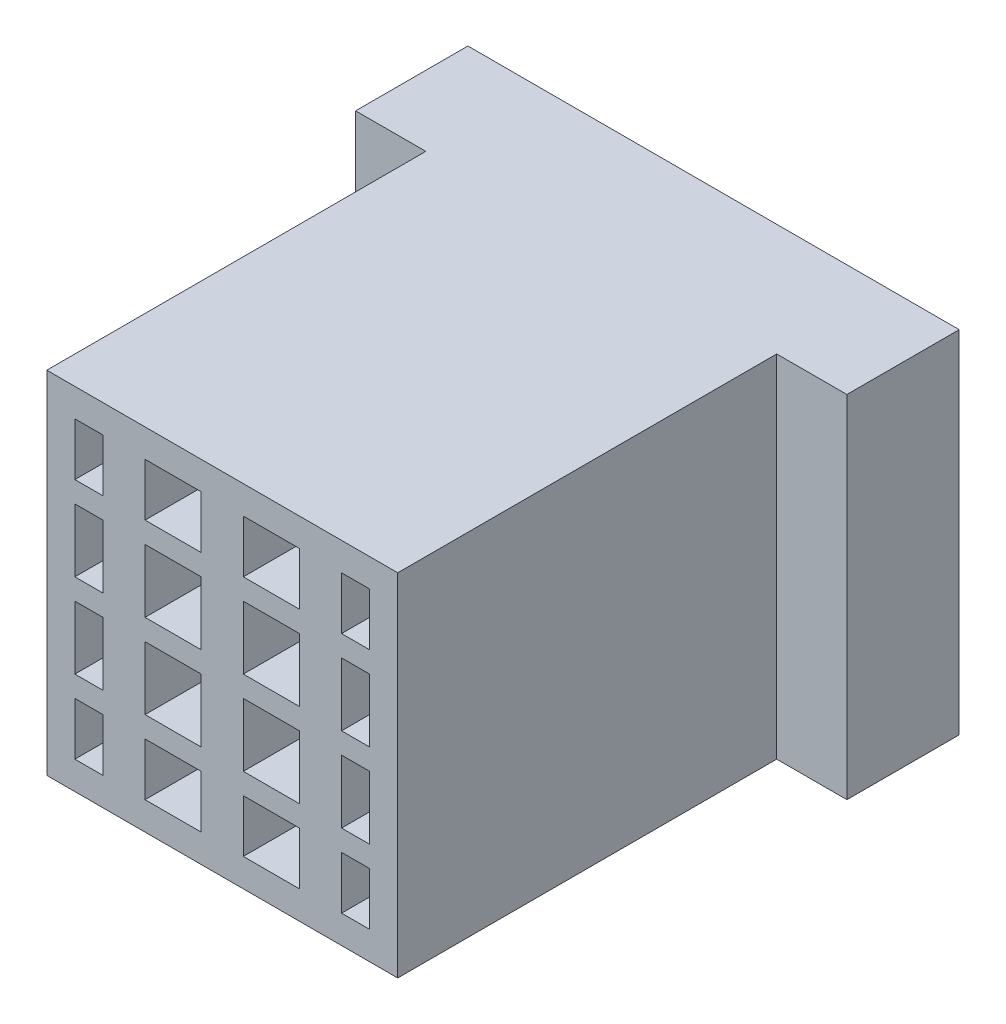
SolidWorks part; units mm, degrees
ref_plane "前视基准面" through (0, 0, 0) normal (0, 0, 1) x (1, 0, 0)
ref_plane "上视基准面" through (0, 0, 0) normal (0, 1, 0) x (1, 0, 0)
ref_plane "右视基准面" through (0, 0, 0) normal (1, 0, 0) x (0, 0, -1)
sketch "草图8" plane through (0, 0, 0) normal (0, 0, 1) x (1, 0, 0)
  line L0 (0, 7.8741) -> (0, -9.2542) construction
  line L1 (-12.5, -12.5) -> (12.5, -12.5)
  line L2 (-12.5, -12.5) -> (-12.5, 12.5)
  line L3 (-12.5, 12.5) -> (12.5, 12.5)
  line L4 (12.5, -12.5) -> (12.5, 12.5)
  line L5 (-12.5, -12.5) -> (12.5, 12.5) construction
  line L6 (-12.5, 12.5) -> (12.5, -12.5) construction
  line L7 (-16.0619, 0) -> (15.5648, 0) construction
  line L8 (-3.5, 7.8741) -> (-3.5, -9.2542) construction
  line L9 (-9.5, 7.8741) -> (-9.5, -9.2542) construction
  line L10 (5.5, 10.5) -> (1.5, 10.5)
  line L15 (-5.5, -10.5) -> (-1.5, -10.5)
  line L20 (-5.5, -10.5) -> (-5.5, 10.5)
  line L21 (-5.5, 10.5) -> (-1.5, 10.5)
  line L26 (-1.5, -10.5) -> (-1.5, 10.5)
  line L27 (-5.5, -10.5) -> (-1.5, 10.5) construction
  line L28 (-5.5, 10.5) -> (-1.5, -10.5) construction
  line L29 (-10.5, -10.5) -> (-8.5, -10.5)
  line L30 (-10.5, -10.5) -> (-10.5, 10.5)
  line L31 (-10.5, 10.5) -> (-8.5, 10.5)
  line L32 (-8.5, -10.5) -> (-8.5, 10.5)
  line L33 (-10.5, -10.5) -> (-8.5, 10.5) construction
  line L34 (-10.5, 10.5) -> (-8.5, -10.5) construction
  line L35 (1.5, -10.5) -> (1.5, 10.5)
  line L36 (5.5, -10.5) -> (1.5, -10.5)
  line L37 (5.5, -10.5) -> (5.5, 10.5)
  line L38 (10.5, 10.5) -> (8.5, 10.5)
  line L39 (8.5, -10.5) -> (8.5, 10.5)
  line L40 (10.5, -10.5) -> (8.5, -10.5)
  line L41 (10.5, -10.5) -> (10.5, 10.5)
  point P0 (0, 0)
  point P14 (-7, 0)
  point P15 (-3.5, 0)
  point P17 (-3, 0)
  point P21 (-9.5, 0)
  point P22 (-9, 0)
  dimension "D1" = 3.5
  dimension "D2" = 6
extrude "凸台-拉伸7" add sketch "草图8" along normal blind 25
sketch "草图9" plane through (0, 0, 0) normal (0, 0, -1) x (-1, 0, 0)
  line L1 (-12.5, -12.5) -> (12.5, -12.5)
  line L2 (-12.5, -12.5) -> (-12.5, 12.5)
  line L3 (-12.5, 12.5) -> (12.5, 12.5)
  line L4 (12.5, -12.5) -> (12.5, 12.5)
  line L5 (-12.5, -12.5) -> (12.5, 12.5) construction
  line L6 (-12.5, 12.5) -> (12.5, -12.5) construction
  point P0 (0, 0)
extrude "凸台-拉伸8" add sketch "草图9" along normal blind 2
sketch "草图11" plane through (0, 0, -2) normal (0, 0, -1) x (-1, 0, 0)
  line L5 (-17.5, -12.5) -> (17.5, -12.5)
  line L6 (-17.5, -12.5) -> (-17.5, 12.5)
  line L7 (-17.5, 12.5) -> (17.5, 12.5)
  line L8 (17.5, -12.5) -> (17.5, 12.5)
  line L9 (-17.5, -12.5) -> (17.5, 12.5) construction
  line L10 (-17.5, 12.5) -> (17.5, -12.5) construction
  point P0 (0, 0)
extrude "凸台-拉伸9" add sketch "草图11" along normal blind 6
sketch "草图12" plane through (0, 0, -8) normal (0, 0, -1) x (-1, 0, 0)
  line L1 (-15, -10.5) -> (15, -10.5)
  line L2 (-15, -10.5) -> (-15, 10.5)
  line L3 (-15, 10.5) -> (15, 10.5)
  line L4 (15, -10.5) -> (15, 10.5)
  line L5 (-15, -10.5) -> (15, 10.5) construction
  line L6 (-15, 10.5) -> (15, -10.5) construction
  point P0 (0, 0)
extrude "切除-拉伸1" cut sketch "草图12" against normal blind 4
sketch "草图14" plane through (0, 0, 25) normal (0, 0, 1) x (1, 0, 0)
  line L0 (-16.6961, 0) -> (20.7273, 0) construction
  line L1 (-12.5, 12.5) -> (-12.5, -12.5) construction
  line L2 (12.5, -0.75) -> (-12.5, -0.75)
  line L3 (12.5, -0.75) -> (12.5, 0.75)
  line L4 (12.5, 0.75) -> (-12.5, 0.75)
  line L5 (-12.5, -0.75) -> (-12.5, 0.75)
  line L6 (12.5, -0.75) -> (-12.5, 0.75) construction
  line L7 (12.5, 0.75) -> (-12.5, -0.75) construction
  line L12 (12.5, 5.25) -> (-12.5, 5.25)
  line L13 (12.5, 5.25) -> (12.5, 6.75)
  line L14 (12.5, 6.75) -> (-12.5, 6.75)
  line L15 (-12.5, 5.25) -> (-12.5, 6.75)
  line L16 (12.5, 5.25) -> (-12.5, 6.75) construction
  line L17 (12.5, 6.75) -> (-12.5, 5.25) construction
  line L18 (12.5, -6.75) -> (-12.5, -5.25) construction
  line L19 (12.5, -5.25) -> (-12.5, -6.75) construction
  line L20 (-12.5, -5.25) -> (-12.5, -6.75)
  line L21 (12.5, -6.75) -> (-12.5, -6.75)
  line L22 (12.5, -5.25) -> (12.5, -6.75)
  line L23 (12.5, -5.25) -> (-12.5, -5.25)
  point P3 (0, 0)
  point P11 (0, 6)
  point P19 (0, -6)
  dimension "D1" = 2
extrude "凸台-拉伸11" add sketch "草图14" against normal blind 25
sketch "草图15" plane through (0, 0, -8) normal (0, 0, -1) x (-1, 0, 0)
  line L1 (-17.5, -12.5) -> (17.5, -12.5)
  line L2 (-17.5, -12.5) -> (-17.5, 12.5)
  line L3 (-17.5, 12.5) -> (17.5, 12.5)
  line L4 (17.5, -12.5) -> (17.5, 12.5)
  line L5 (-17.5, -12.5) -> (17.5, 12.5) construction
  line L6 (-17.5, 12.5) -> (17.5, -12.5) construction
  point P0 (0, 0)
extrude "凸台-拉伸12" add sketch "草图15" along normal blind 2
sketch "草图16" plane through (0, 12.5, 0) normal (0, 1, 0) x (1, 0, 0)
  line L0 (-7.0185, -25) -> (-7.0185, 10)
  line L1 (12.5, -25) -> (-12.5, -25) construction
  line L2 (-17.5, 10) -> (17.5, 10) construction
  line L3 (-12.5, -20) -> (12.5, -20)
  line L4 (-12.5, -25) -> (-12.5, 2) construction
  line L5 (12.5, -25) -> (12.5, 2) construction
  dimension "D1" = 5
sketch "草图17" plane through (0, -12.5, 0) normal (0, -1, 0) x (1, 0, 0)
  line L0 (-12.5, 20) -> (12.5, 20)
  line L1 (-7.0185, 25) -> (-7.0185, -10)
